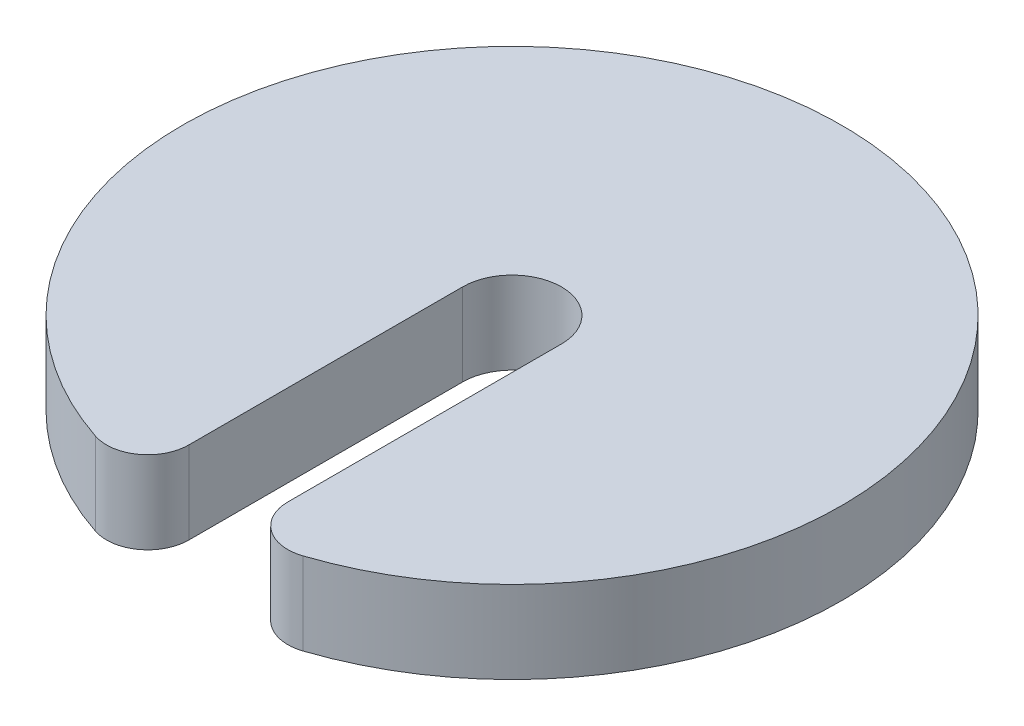
SolidWorks part; units mm, degrees
ref_plane "Front Plane" through (0, 0, 0) normal (0, 0, 1) x (1, 0, 0)
ref_plane "Top Plane" through (0, 0, 0) normal (0, 1, 0) x (1, 0, 0)
ref_plane "Right Plane" through (0, 0, 0) normal (1, 0, 0) x (0, 0, -1)
sketch "Sketch1" plane through (0, 0, 0) normal (0, 1, 0) x (1, 0, 0)
  line L0 (6, 0) -> (6, -33.2265)
  line L1 (-6, 0) -> (-6, -33.2265)
  arc A0 (12.5714, -37.9731) -> (-12.5714, -37.9731) centre (0, 0) ccw
  arc A1 (6, 0) -> (-6, 0) centre (0, 0) ccw
  arc A2 (6, -33.2265) -> (12.5714, -37.9731) centre (11, -33.2265) ccw
  arc A3 (-6, -33.2265) -> (-12.5714, -37.9731) centre (-11, -33.2265) cw
  dimension "D1" = 80
  dimension "D2" = 12
  dimension "D3" = 5
extrude "Boss-Extrude1" add sketch "Sketch1" along normal blind 10
